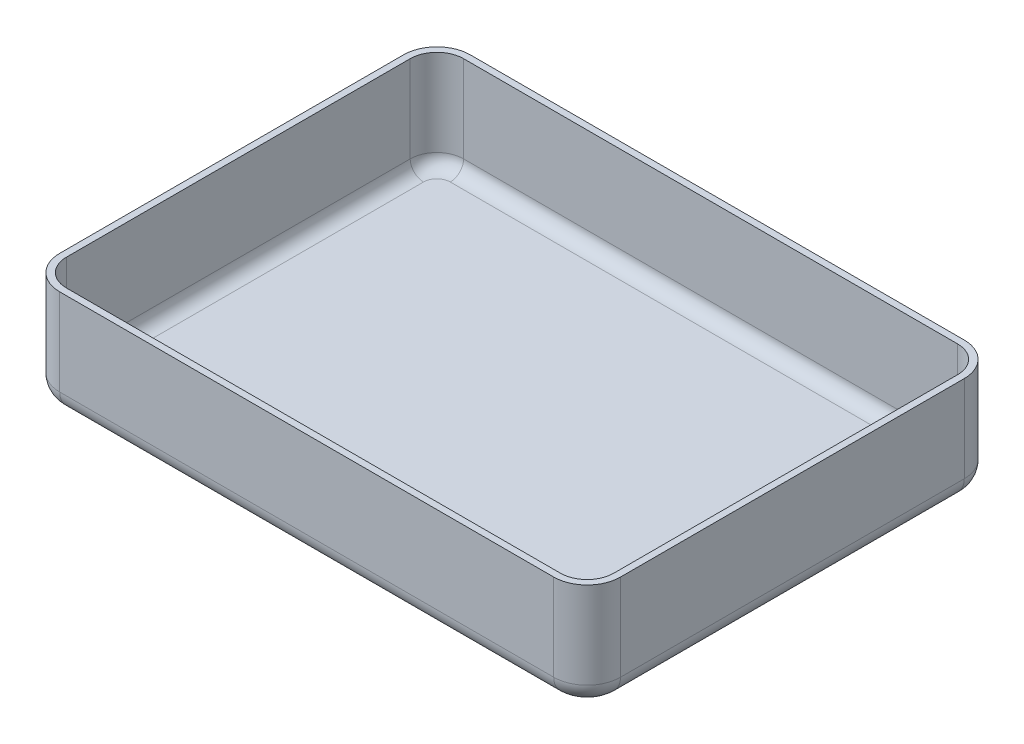
SolidWorks part; units mm, degrees
material "ABS"
ref_plane "Front Plane" through (0, 0, 0) normal (0, 0, 1) x (1, 0, 0)
ref_plane "Top Plane" through (0, 0, 0) normal (0, 1, 0) x (1, 0, 0)
ref_plane "Right Plane" through (0, 0, 0) normal (1, 0, 0) x (0, 0, -1)
sketch "Sketch1" plane through (0, 0, 0) normal (0, 1, 0) x (1, 0, 0)
  line L0 (0, 59.5) -> (0, 0) construction
  line L1 (-74, 59.5) -> (74, 59.5)
  line L2 (-82, 51.5) -> (-82, -51.5)
  line L3 (-74, -59.5) -> (74, -59.5)
  line L4 (82, 51.5) -> (82, -51.5)
  line L5 (0, 0) -> (0, -59.5) construction
  arc A0 (74, 59.5) -> (82, 51.5) centre (74, 51.5) cw
  arc A1 (82, -51.5) -> (74, -59.5) centre (74, -51.5) cw
  arc A2 (-74, -59.5) -> (-82, -51.5) centre (-74, -51.5) cw
  arc A3 (-82, 51.5) -> (-74, 59.5) centre (-74, 51.5) cw
  dimension "D1" = 8
  dimension "D2" = 119
  dimension "D3" = 164
extrude "Boss-Extrude1" add sketch "Sketch1" against normal mid plane 30
fillet "Fillet1" radius 4 8 edges at (0, -15, -59.5) (-79.6569, -15, -57.1569) (-82, -15, 0) (-79.6569, -15, 57.1569) (0, -15, 59.5) (79.6569, -15, 57.1569) (82, -15, 0) (79.6569, -15, -57.1569)
shell "Shell1" thickness 2
